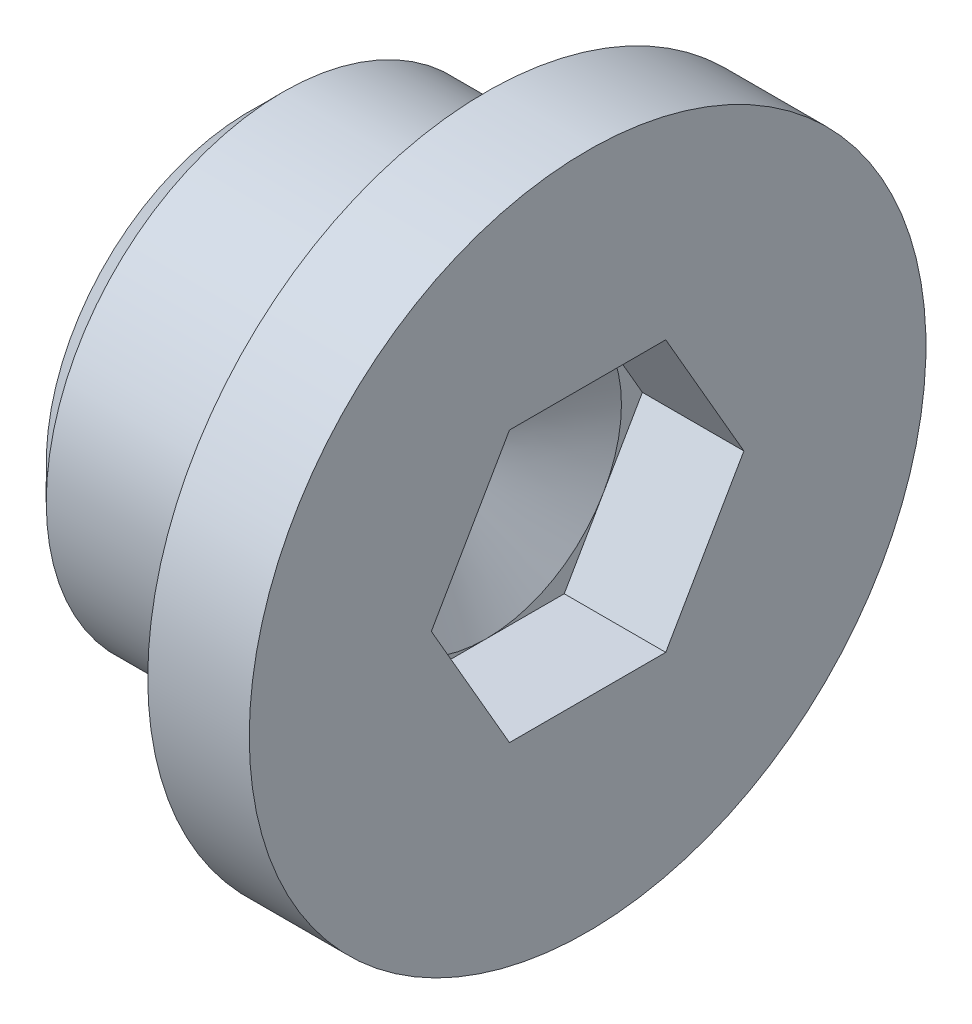
SolidWorks part; units mm, degrees
ref_plane "Plan de face" through (0, 0, 0) normal (0, 0, 1) x (1, 0, 0)
ref_plane "Plan de dessus" through (0, 0, 0) normal (0, 1, 0) x (1, 0, 0)
ref_plane "Plan de droite" through (0, 0, 0) normal (1, 0, 0) x (0, 0, -1)
sketch "Esquisse1" plane through (0, 0, 0) normal (0, 0, 1) x (1, 0, 0)
  line L0 (0, 0) -> (109.7255, 0) construction
  line L1 (0, 0) -> (0, 7)
  line L2 (0, 7) -> (5.9838, 7)
  line L3 (7, 7) -> (7, 10)
  line L4 (7, 10) -> (10, 10)
  line L5 (10, 10) -> (10, 0)
  line L6 (0, 0) -> (10, 0)
  arc A0 (5.9838, 7) -> (7, 7) centre (6.4919, 7) ccw
  dimension "D1" = 7
  dimension "D2" = 7
  dimension "D3" = 3
  dimension "D4" = 10
revolve "Révolution1" add sketch "Esquisse1" angle 360 about L0
cosmetic thread "Représentation de filetage1" parameters "D2"=12
sketch "Esquisse3" plane through (10, 0, 0) normal (1, 0, 0) x (0, 0, -1)
  line L0 (6.1678, 0) -> (-6.1678, 0) construction
  line L1 (-4.6188, 0) -> (-2.3094, 4)
  line L2 (0, 0) -> (-2.6829, 4.6469) construction
  line L3 (0, 0) -> (0, 6.5135) construction
  line L4 (0, 0) -> (2.6829, 4.6469) construction
  line L5 (4.6188, 0) -> (2.3094, 4)
  line L6 (-2.3094, 4) -> (2.3094, 4)
  line L7 (4.6188, 0) -> (2.3094, -4)
  line L8 (-2.3094, -4) -> (2.3094, -4)
  line L9 (-4.6188, 0) -> (-2.3094, -4)
  dimension "D1" = 60
  dimension "D2" = 4
hole_wizard "Diamètre du perçage Ø8.0 (8)1" positions "Esquisse3D2" profile "Esquisse5" hole size "Ø8.0" standard "Ansi Métrique"
sketch3d "Esquisse3D2"
  point P0 (0, 0, 0)
  point P4 (10, 0, 0)
sketch "Esquisse5" plane through (10, 0, 0) normal (0, 1, 0) x (0, 0, -1)
  line L0 (0, 0) -> (0, 5.4034)
  line L1 (0, 5.4034) -> (4, 3)
  line L2 (4, 3) -> (4, 0)
  line L5 (4, 0) -> (0, 0)
  line L10 (0, 5.4034) -> (-4, 3) construction
  line L11 (0, -6.35) -> (0, 107.95) construction
  dimension "Diamètre du perçage" = 8
  dimension "Profondeur du perçage" = 3
  dimension "Angle de pointe" = 118
extrude "Enlèv. mat.-Extru.1" cut sketch "Esquisse3" against normal blind 3
chamfer "Chanfrein1" distance 1 angle 45 1 edges at (0, 0, 7)
